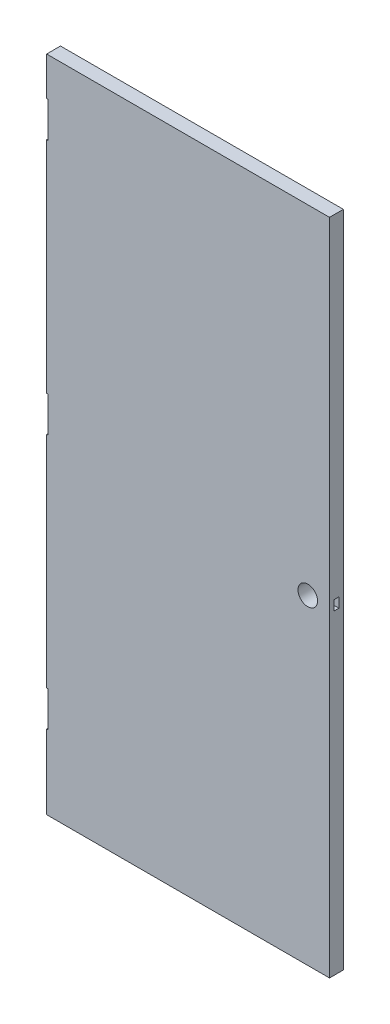
SolidWorks part; units mm, degrees
ref_plane "Front Plane" through (0, 0, 0) normal (0, 0, 1) x (1, 0, 0)
ref_plane "Top Plane" through (0, 0, 0) normal (0, 1, 0) x (1, 0, 0)
ref_plane "Right Plane" through (0, 0, 0) normal (1, 0, 0) x (0, 0, -1)
sketch "Sketch1" plane through (0, 0, 0) normal (0, 0, 1) x (1, 0, 0)
  line L0 (-454.025, 819.15) -> (-449.453, 819.15) construction
  line L1 (454.025, -1057.275) -> (-454.025, -1057.275)
  line L2 (454.025, -1057.275) -> (454.025, 1057.275)
  line L3 (454.025, 1057.275) -> (-454.025, 1057.275)
  line L4 (-454.025, -1057.275) -> (-454.025, 1057.275)
  line L5 (454.025, -1057.275) -> (-454.025, 1057.275) construction
  line L6 (454.025, 1057.275) -> (-454.025, -1057.275) construction
  circle A0 centre (384.175, -28.575) radius 31.4325
  point P0 (0, 0)
  point P5 (-454.025, 933.45)
  point P6 (-454.025, 114.3)
  point P8 (-454.025, -704.85)
  point P9 (-454.025, 819.15)
  point P15 (-454.025, 1057.275)
  dimension "D1" = 62.865
  dimension "Wd" = 908.05
  dimension "Ht" = 2114.55
  dimension "A" = 123.825
  dimension "B" = 942.975
  dimension "C" = 1762.125
  dimension "Hinge Leaf Ht" = 114.3
  dimension "Hinge Leaf Thk" = 4.572
  dimension "Handle Backset" = 69.85
  dimension "Top to Handle" = 1085.85
sketch "Sketch2" plane through (0, 0, 0) normal (1, 0, 0) x (0, 0, -1)
  line L0 (-22.225, 0) -> (22.225, 0) construction
  line L1 (-22.225, 1057.275) -> (22.225, 1057.275) construction
  dimension "Door Thk" = 44.45
sketch "Sketch3" plane through (0, 0, 0) normal (0, 0, 1) x (1, 0, 0)
  line L0 (454.025, -1057.275) -> (454.025, 1057.275) construction
  line L1 (454.025, -1057.275) -> (-454.025, -1057.275) construction
  line L3 (454.025, 1057.275) -> (-454.025, 1057.275) construction
  line L4 (454.025, -1057.275) -> (454.025, 1057.275)
  line L5 (454.025, -1057.275) -> (-454.025, -1057.275)
  line L7 (454.025, 1057.275) -> (-454.025, 1057.275)
  line L8 (-454.025, -1057.275) -> (-454.025, 1057.275) construction
  line L9 (-449.453, 819.15) -> (-454.025, 819.15)
  line L10 (-449.453, 819.15) -> (-449.453, 933.45)
  line L11 (-449.453, 933.45) -> (-454.025, 933.45)
  line L13 (-454.025, 114.3) -> (-449.453, 114.3)
  line L15 (-454.025, 0) -> (-449.453, 0)
  line L16 (-449.453, 114.3) -> (-449.453, 0)
  line L17 (-454.025, -704.85) -> (-449.453, -704.85)
  line L19 (-454.025, -819.15) -> (-449.453, -819.15)
  line L20 (-449.453, -704.85) -> (-449.453, -819.15)
  line L21 (-454.025, -1057.275) -> (-454.025, -819.15)
  line L22 (-454.025, -704.85) -> (-454.025, 0)
  line L23 (-454.025, 114.3) -> (-454.025, 819.15)
  line L24 (-454.025, 933.45) -> (-454.025, 1057.275)
  circle A0 centre (384.175, -28.575) radius 31.4325 construction
  circle A1 centre (384.175, -28.575) radius 31.4325
extrude "Boss-Extrude1" add sketch "Sketch3" against normal up to vertex (22.225 mm away) and the other way up to vertex (22.225 mm away) up to point (0, 0, -22.225) other way up to point (0, 0, 22.225)
sketch "Sketch4" plane through (454.025, 0, 0) normal (1, 0, 0) x (0, 0, -1)
  line L0 (0, -1057.275) -> (0, 1057.275) construction
  line L1 (7.8581, -44.2913) -> (-7.8581, -44.2913)
  line L2 (7.8581, -44.2913) -> (7.8581, -12.8588)
  line L3 (7.8581, -12.8588) -> (-7.8581, -12.8588)
  line L4 (-7.8581, -44.2913) -> (-7.8581, -12.8588)
  line L5 (7.8581, -44.2913) -> (-7.8581, -12.8588) construction
  line L6 (7.8581, -12.8588) -> (-7.8581, -44.2913) construction
  point P0 (0, -28.575)
  dimension "D1" = 31.4325
  dimension "D2" = 15.7163
extrude "Cut-Extrude1" cut sketch "Sketch4" against normal up to next
equation "\"D1@Sketch1\"=\"Handle Backset@Sketch1\"*.9"
equation "\"D1@Sketch4\"=\"D1@Sketch1\"*.5"
equation "\"D2@Sketch4\"=\"D1@Sketch4\"*.5"
